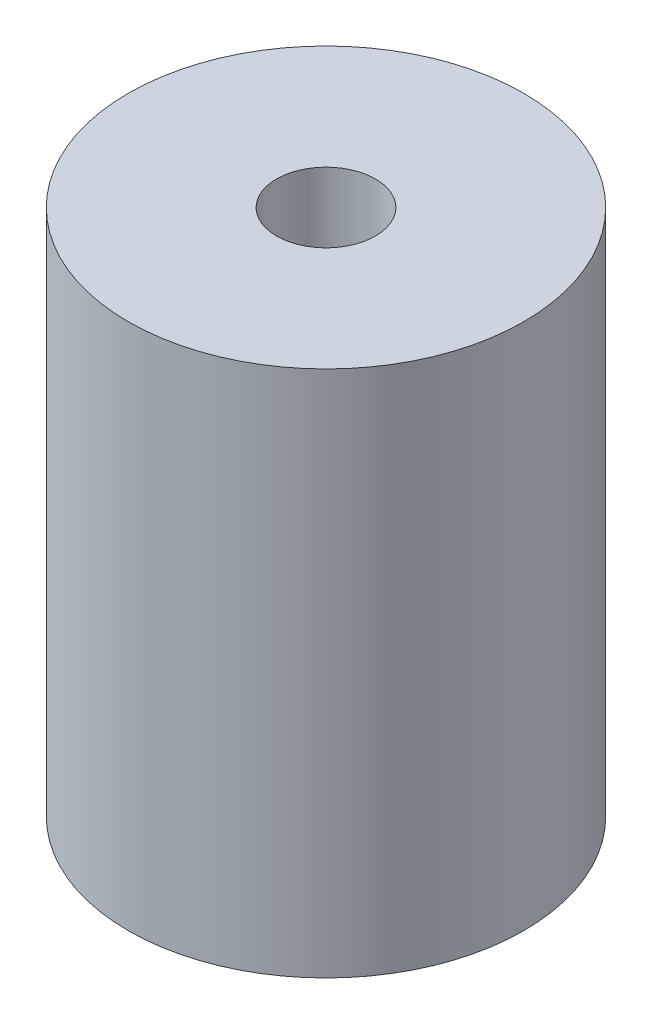
SolidWorks part; units mm, degrees
ref_plane "Front Plane" through (0, 0, 0) normal (0, 0, 1) x (1, 0, 0)
ref_plane "Top Plane" through (0, 0, 0) normal (0, 1, 0) x (1, 0, 0)
ref_plane "Right Plane" through (0, 0, 0) normal (1, 0, 0) x (0, 0, -1)
sketch "Sketch1" plane through (0, 0, 0) normal (0, 1, 0) x (1, 0, 0)
  circle A0 centre (0, 0) radius 9.525
  dimension "D1" = 19.05
extrude "Boss-Extrude1" add sketch "Sketch1" along normal blind 25.4
sketch "Sketch2" plane through (0, 25.4, 0) normal (0, 1, 0) x (1, 0, 0)
  circle A0 centre (0, 0) radius 2.3813
  dimension "D1" = 4.7625
extrude "Cut-Extrude1" cut sketch "Sketch2" against normal blind 12.7
sketch "Sketch3" plane through (0, 0, 0) normal (0, -1, 0) x (1, 0, 0)
  circle A0 centre (0, 0) radius 3.175
  dimension "D1" = 6.35
extrude "Cut-Extrude2" cut sketch "Sketch3" against normal blind 12.7
